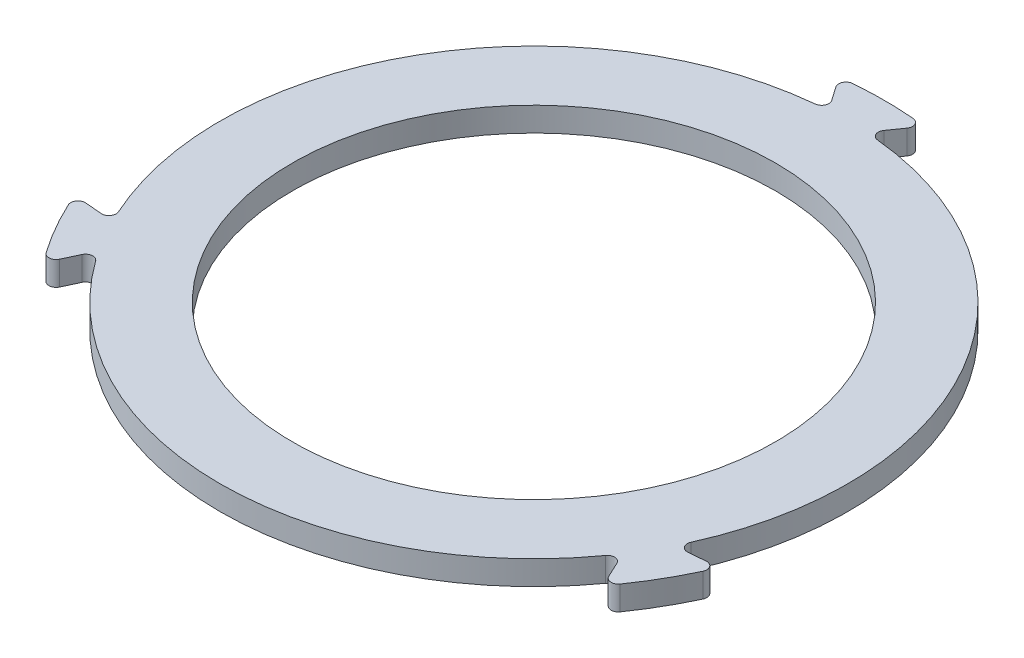
SolidWorks part; units mm, degrees
ref_plane "Front Plane" through (0, 0, 0) normal (0, 0, 1) x (1, 0, 0)
ref_plane "Top Plane" through (0, 0, 0) normal (0, 1, 0) x (1, 0, 0)
ref_plane "Right Plane" through (0, 0, 0) normal (1, 0, 0) x (0, 0, -1)
sketch "Sketch2" plane through (0, 0, 0) normal (1, 0, 0) x (0, 0, -1)
  line L0 (-50, 0) -> (-65, 0)
  line L1 (-65, 0) -> (-65, 5)
  line L2 (-65, 5) -> (-50, 5)
  line L5 (-50, 5) -> (-50, 0)
  dimension "D1" = 65
  dimension "D2" = 5
  dimension "D4" = 15
ref_axis "Axis1" through (0, -0.75, 0) along (0, 1, 0)
revolve "Revolve1" add sketch "Sketch2" angle 360 about axis through (0, -0.75, 0) along (0, 1, 0)
sketch "Sketch4" plane through (0, 5, 0) normal (0, 1, 0) x (1, 0, 0)
  line L0 (0, 0) -> (0, 84.4218) construction
  line L1 (-3.8812, 64.884) -> (-8.8355, 71.9596)
  line L2 (8.8355, 71.9596) -> (3.8812, 64.884)
  line L3 (-3.8812, 64.884) -> (0, 59.3412) construction
  line L4 (0, 0) -> (-8.8355, 71.9596) construction
  arc A0 (-3.8812, 64.884) -> (3.8812, 64.884) centre (0, 0) cw
  arc A2 (-8.8355, 71.9596) -> (8.8355, 71.9596) centre (0, 0) cw
  circle A3 centre (0, 0) radius 65 construction
  dimension "D1" = 35
  dimension "D2" = 7.5
  dimension "D3" = 7
  dimension "D4" = 130
extrude "Boss-Extrude1" add sketch "Sketch4" against normal blind 5
fillet "Fillet2" radius 1.5 4 edges at (-3.8812, 2.5, -64.884) (-8.8355, 2.5, -71.9596) (8.8355, 2.5, -71.9596) (3.8812, 2.5, -64.884)
pattern_circular "CirPattern4" count 3 over 360 about axis through (0, 0, 0) along (0, 1, 0) of "Fillet2", "Boss-Extrude1"
